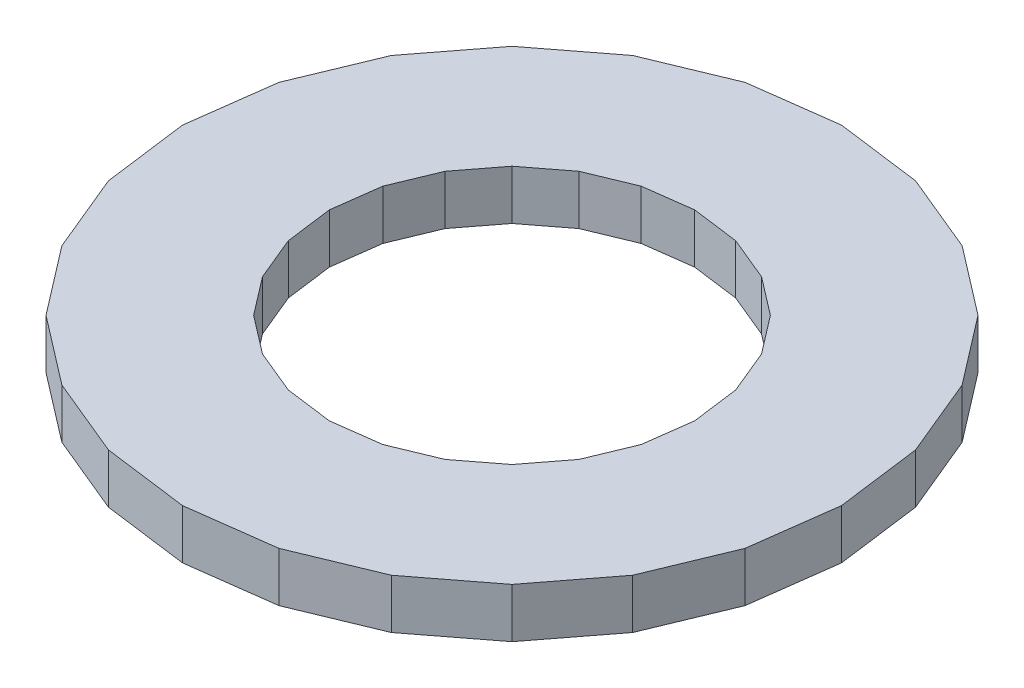
SolidWorks part; units mm, degrees
ref_plane "Front Plane" through (0, 0, 0) normal (0, 0, 1) x (1, 0, 0)
ref_plane "Top Plane" through (0, 0, 0) normal (0, 1, 0) x (1, 0, 0)
ref_plane "Right Plane" through (0, 0, 0) normal (1, 0, 0) x (0, 0, -1)
sketch "Sketch3" plane through (0, 0, 0) normal (0, 1, 0) x (1, 0, 0)
  line L0 (0, 0) -> (-70.1258, 0) construction
  line L1 (-126.488, 0) -> (-122.178, -32.7375)
  line L2 (-122.178, -32.7375) -> (-109.5418, -63.244)
  line L3 (-109.5418, -63.244) -> (-89.4405, -89.4405)
  line L4 (-89.4405, -89.4405) -> (-63.244, -109.5418)
  line L5 (-63.244, -109.5418) -> (-32.7375, -122.178)
  line L6 (-32.7375, -122.178) -> (0, -126.488)
  line L7 (0, -126.488) -> (32.7375, -122.178)
  line L8 (32.7375, -122.178) -> (63.244, -109.5418)
  line L9 (63.244, -109.5418) -> (89.4405, -89.4405)
  line L10 (89.4405, -89.4405) -> (109.5418, -63.244)
  line L11 (109.5418, -63.244) -> (122.178, -32.7375)
  line L12 (122.178, -32.7375) -> (126.488, 0)
  line L13 (126.488, 0) -> (122.178, 32.7375)
  line L14 (122.178, 32.7375) -> (109.5418, 63.244)
  line L15 (109.5418, 63.244) -> (89.4405, 89.4405)
  line L16 (89.4405, 89.4405) -> (63.244, 109.5418)
  line L17 (63.244, 109.5418) -> (32.7375, 122.178)
  line L18 (32.7375, 122.178) -> (0, 126.488)
  line L19 (0, 126.488) -> (-32.7375, 122.178)
  line L20 (-32.7375, 122.178) -> (-63.244, 109.5418)
  line L21 (-63.244, 109.5418) -> (-89.4405, 89.4405)
  line L22 (-89.4405, 89.4405) -> (-109.5418, 63.244)
  line L23 (-109.5418, 63.244) -> (-122.178, 32.7375)
  line L24 (-122.178, 32.7375) -> (-126.488, 0)
  line L25 (-70.1258, 0) -> (-67.7364, -18.1499)
  line L26 (-67.7364, -18.1499) -> (-60.7308, -35.0629)
  line L27 (-60.7308, -35.0629) -> (-49.5865, -49.5865)
  line L28 (-49.5865, -49.5865) -> (-35.0629, -60.7308)
  line L29 (-35.0629, -60.7308) -> (-18.1499, -67.7364)
  line L30 (-18.1499, -67.7364) -> (0, -70.1258)
  line L31 (0, -70.1258) -> (18.1499, -67.7364)
  line L32 (18.1499, -67.7364) -> (35.0629, -60.7308)
  line L33 (35.0629, -60.7308) -> (49.5865, -49.5865)
  line L34 (49.5865, -49.5865) -> (60.7308, -35.0629)
  line L35 (60.7308, -35.0629) -> (67.7364, -18.1499)
  line L36 (67.7364, -18.1499) -> (70.1258, 0)
  line L37 (70.1258, 0) -> (67.7364, 18.1499)
  line L38 (67.7364, 18.1499) -> (60.7308, 35.0629)
  line L39 (60.7308, 35.0629) -> (49.5865, 49.5865)
  line L40 (49.5865, 49.5865) -> (35.0629, 60.7308)
  line L41 (35.0629, 60.7308) -> (18.1499, 67.7364)
  line L42 (18.1499, 67.7364) -> (0, 70.1258)
  line L43 (0, 70.1258) -> (-18.1499, 67.7364)
  line L44 (-18.1499, 67.7364) -> (-35.0629, 60.7308)
  line L45 (-35.0629, 60.7308) -> (-49.5865, 49.5865)
  line L46 (-49.5865, 49.5865) -> (-60.7308, 35.0629)
  line L47 (-60.7308, 35.0629) -> (-67.7364, 18.1499)
  line L48 (-67.7364, 18.1499) -> (-70.1258, 0)
  line L49 (-126.488, 0) -> (-70.1258, 0) construction
  circle A0 centre (0, 0) radius 125.4059 construction
  circle A1 centre (0, 0) radius 69.5259 construction
  dimension "D1" = 33.02
  dimension "D2" = 55.88
extrude "Boss-Extrude3" add sketch "Sketch3" along normal blind 19.05
